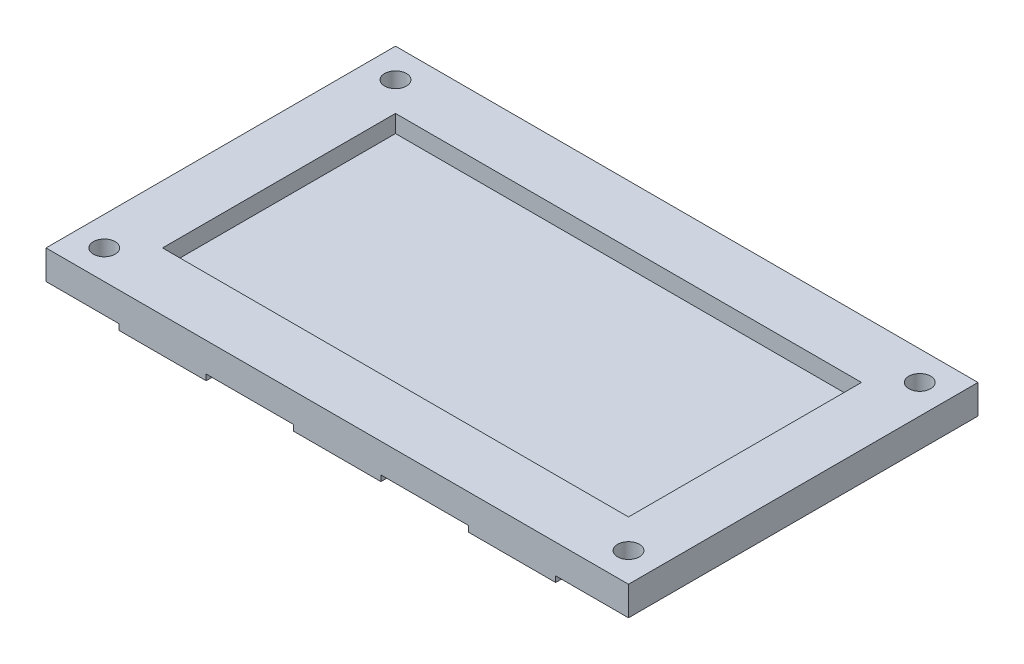
SolidWorks part; units mm, degrees
ref_plane "Front Plane" through (0, 0, 0) normal (0, 0, 1) x (1, 0, 0)
ref_plane "Top Plane" through (0, 0, 0) normal (0, 1, 0) x (1, 0, 0)
ref_plane "Right Plane" through (0, 0, 0) normal (1, 0, 0) x (0, 0, -1)
sketch "Sketch1" plane through (0, 0, 0) normal (0, 1, 0) x (1, 0, 0)
  line L1 (100, -60) -> (-100, -60)
  line L2 (100, -60) -> (100, 60)
  line L3 (100, 60) -> (-100, 60)
  line L4 (-100, -60) -> (-100, 60)
  line L5 (100, -60) -> (-100, 60) construction
  line L6 (100, 60) -> (-100, -60) construction
  point P0 (0, 0)
  dimension "D1" = 200
  dimension "D2" = 120
extrude "Boss-Extrude3" add sketch "Sketch1" along normal blind 10
sketch "Sketch3" plane through (0, 10, 0) normal (0, 1, 0) x (1, 0, 0)
  line L0 (-100, 60) -> (-80, 40) construction
  line L1 (-80, 40) -> (80, 40)
  line L2 (-80, 40) -> (-80, -40)
  line L3 (-80, -40) -> (80, -40)
  line L4 (80, 40) -> (80, -40)
  line L5 (-80, 40) -> (80, -40) construction
  line L6 (-80, -40) -> (80, 40) construction
  line L7 (80, 40) -> (100, 60) construction
  line L8 (-80, -40) -> (-100, -60) construction
  line L12 (80, -40) -> (100, -60) construction
  circle A0 centre (-90, 50) radius 3.75
  circle A2 centre (90, -50) radius 3.75
  circle A4 centre (90, 50) radius 3.75
  circle A5 centre (-90, -50) radius 3.75
  point P0 (0, 0)
  point P19 (0, 0)
  dimension "D3" = 7.5
  dimension "D4" = 7.5
  dimension "D5" = 7.5
  dimension "D6" = 7.5
  dimension "D1" = 160
  dimension "D2" = 80
extrude "Cut-Extrude2" cut sketch "Sketch3" along direction (0, 1, 0) on the side against the normal blind 6
sketch "Sketch6" plane through (0, 4, 0) normal (0, 1, 0) x (1, 0, 0)
  circle A0 centre (-90, 50) radius 3.75
  circle A1 centre (90, 50) radius 3.75
  circle A2 centre (90, -50) radius 3.75
  circle A3 centre (-90, -50) radius 3.75
  dimension "D1" = 7.5
  dimension "D2" = 7.5
  dimension "D3" = 7.5
  dimension "D4" = 7.5
extrude "Cut-Extrude4" cut sketch "Sketch6" against normal through all
sketch "Sketch7" plane through (0, 0, 0) normal (0, -1, 0) x (-1, 0, 0)
  line L0 (-100, 60) -> (100, 60) construction
  line L1 (15, -60) -> (-15, -60)
  line L2 (15, -60) -> (15, 60)
  line L3 (15, 60) -> (-15, 60)
  line L4 (-15, -60) -> (-15, 60)
  line L5 (15, -60) -> (-15, 60) construction
  line L6 (15, 60) -> (-15, -60) construction
  line L7 (75, -60) -> (75, 60)
  line L8 (75, -60) -> (45, -60)
  line L9 (45, -60) -> (45, 60)
  line L10 (75, 60) -> (45, 60)
  line L11 (-45, -60) -> (-45, 60)
  line L12 (-45, -60) -> (-75, -60)
  line L13 (-75, -60) -> (-75, 60)
  line L14 (-45, 60) -> (-75, 60)
  point P0 (0, 0)
  dimension "D1" = 30
  dimension "D2" = 2
  dimension "D3" = 2
extrude "Boss-Extrude4" add sketch "Sketch7" along normal blind 2
sketch "Sketch8" plane through (0, -2, 0) normal (0, -1, 0) x (-1, 0, 0)
  line L0 (119.8072, 0) -> (-126.1232, 0) construction
  line L1 (0, -66.4669) -> (0, 75.408) construction
  line L2 (30, -20) -> (20, -20)
  line L3 (30, -20) -> (30, -15)
  line L4 (30, -15) -> (20, -15)
  line L5 (20, -20) -> (20, -15)
  line L6 (30, -20) -> (20, -15) construction
  line L7 (30, -15) -> (20, -20) construction
  line L8 (-30, -15) -> (-20, -15)
  line L9 (-20, -20) -> (-20, -15)
  line L10 (-30, -20) -> (-20, -20)
  line L11 (-30, -20) -> (-30, -15)
  line L12 (-30, 20) -> (-30, 15)
  line L13 (-30, 20) -> (-20, 20)
  line L14 (-20, 20) -> (-20, 15)
  line L15 (-30, 15) -> (-20, 15)
  line L16 (30, 15) -> (20, 15)
  line L17 (20, 20) -> (20, 15)
  line L18 (30, 20) -> (20, 20)
  line L19 (30, 20) -> (30, 15)
  point P3 (25, -17.5)
  dimension "D1" = 25
  dimension "D2" = 17.5
  dimension "D3" = 10
  dimension "D4" = 5
extrude "Boss-Extrude5" add sketch "Sketch8" against normal blind 2 separate body
sketch "Sketch10" plane through (0, -2, 0) normal (0, -1, 0) x (-1, 0, 0)
  line L0 (20, -20) -> (30, -20) construction
  line L1 (30, -20) -> (20, -20)
  line L2 (30, -20) -> (30, -15)
  line L3 (30, -15) -> (20, -15)
  line L4 (20, -20) -> (20, -15)
  line L5 (30, -20) -> (30, -15) construction
  line L6 (20, 20) -> (20, 15) construction
  line L7 (30, 15) -> (20, 15)
  line L8 (30, 15) -> (30, 20)
  line L9 (30, 20) -> (20, 20)
  line L10 (20, 15) -> (20, 20)
  line L11 (30, 20) -> (20, 20) construction
  line L12 (-30, 20) -> (-30, 15) construction
  line L13 (-20, 15) -> (-30, 15)
  line L14 (-20, 15) -> (-20, 20)
  line L15 (-20, 20) -> (-30, 20)
  line L16 (-30, 15) -> (-30, 20)
  line L17 (-20, 20) -> (-30, 20) construction
  line L19 (-20, -20) -> (-30, -20)
  line L20 (-20, -20) -> (-20, -15)
  line L21 (-20, -15) -> (-30, -15)
  line L22 (-30, -20) -> (-30, -15)
extrude "Boss-Extrude6" add sketch "Sketch10" along normal blind 5
